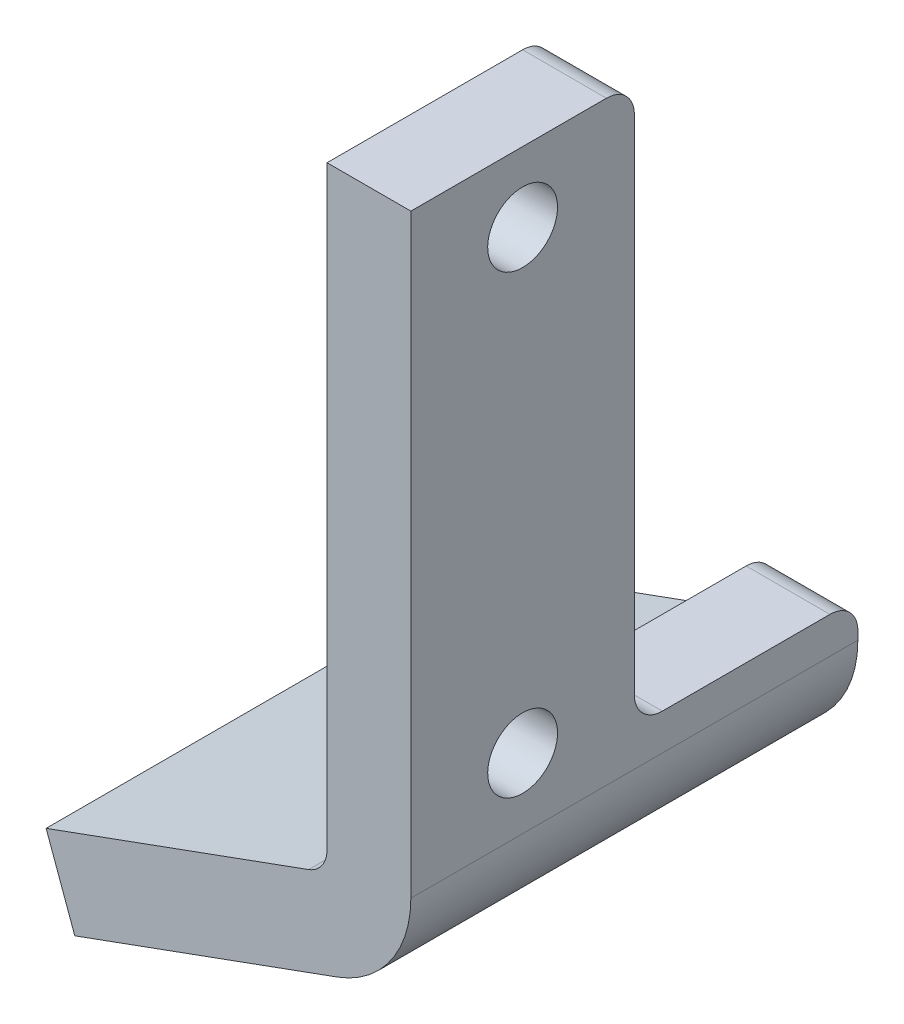
SolidWorks part; units mm, degrees
ref_plane "Front Plane" through (0, 0, 0) normal (0, 0, 1) x (1, 0, 0)
ref_plane "Top Plane" through (0, 0, 0) normal (0, 1, 0) x (1, 0, 0)
ref_plane "Right Plane" through (0, 0, 0) normal (1, 0, 0) x (0, 0, -1)
sketch "Sketch2" plane through (0, 0, 0) normal (0, 0, 1) x (1, 0, 0)
  line L0 (0, 0) -> (0, 16.3) construction
  line L1 (-2.158, -1.9397) -> (-11.5549, -5.3599)
  line L2 (-1.5, 20.3) -> (1.5, 20.3)
  line L3 (-1.5, 20.3) -> (-1.5, -1)
  line L5 (1.5, 20.3) -> (1.5, -1)
  line L6 (-10.5288, -8.179) -> (-1.1319, -4.7588)
  line L7 (-11.5549, -5.3599) -> (-10.5288, -8.179)
  arc A0 (-1.5, -1) -> (-2.158, -1.9397) centre (-2.5, -1) cw
  arc A1 (1.5, -1) -> (-1.1319, -4.7588) centre (-2.5, -1) cw
  point P7 (0, 20.3)
  dimension "D4" = 1
  dimension "D5" = 4
  dimension "D1" = 16.3
  dimension "D2" = 3
  dimension "D3" = 4
  dimension "D6" = 3
  dimension "D7" = 20
  dimension "D8" = 10
  dimension "D9" = 1
extrude "Boss-Extrude2" add sketch "Sketch2" against normal blind 16
sketch "Sketch6" plane through (-1.5, 0, 0) normal (-1, 0, 0) x (0, 0, 1)
  line L0 (0, 20.3) -> (0, -1) construction
  line L1 (-16, 20.3) -> (0, 20.3) construction
  line L2 (-8, 20.3) -> (-8, 0.3)
  line L3 (-8, 0.3) -> (-16, 0.3)
  line L4 (-16, 20.3) -> (-16, -1) construction
  line L5 (-8, 20.3) -> (-16, 20.3)
  line L6 (-16, 20.3) -> (-16, 0.3)
  circle A0 centre (-4, 17.8) radius 1.25
  circle A1 centre (-4, 1.5) radius 1.25
  dimension "D4" = 2.5
  dimension "D1" = 16.3
  dimension "D2" = 4
  dimension "D3" = 2.5
  dimension "D5" = 4
  dimension "D6" = 20
sketch "Sketch7" plane through (0.371, -1.0192, 0) normal (-0.342, 0.9397, 0) x (0.9397, 0.342, 0)
  line L0 (-2.6913, 0) -> (-12.6913, 0) construction
  line L2 (-2.6913, 16) -> (-12.6913, 16) construction
  circle A0 centre (-7.6913, 11) radius 2.25
  point P2 (-7.6736, 7.4838)
  point P5 (-7.6913, 0)
  dimension "D1" = 4.5
  dimension "D2" = 5
extrude "Cut-Extrude4" cut sketch "Sketch7" against normal through all
extrude "Cut-Extrude5" cut sketch "Sketch6" against normal through all
fillet "Fillet2" radius 1 3 edges at (0, 0.3, -16) (0, 0.3, -8) (0, 20.3, -8)
